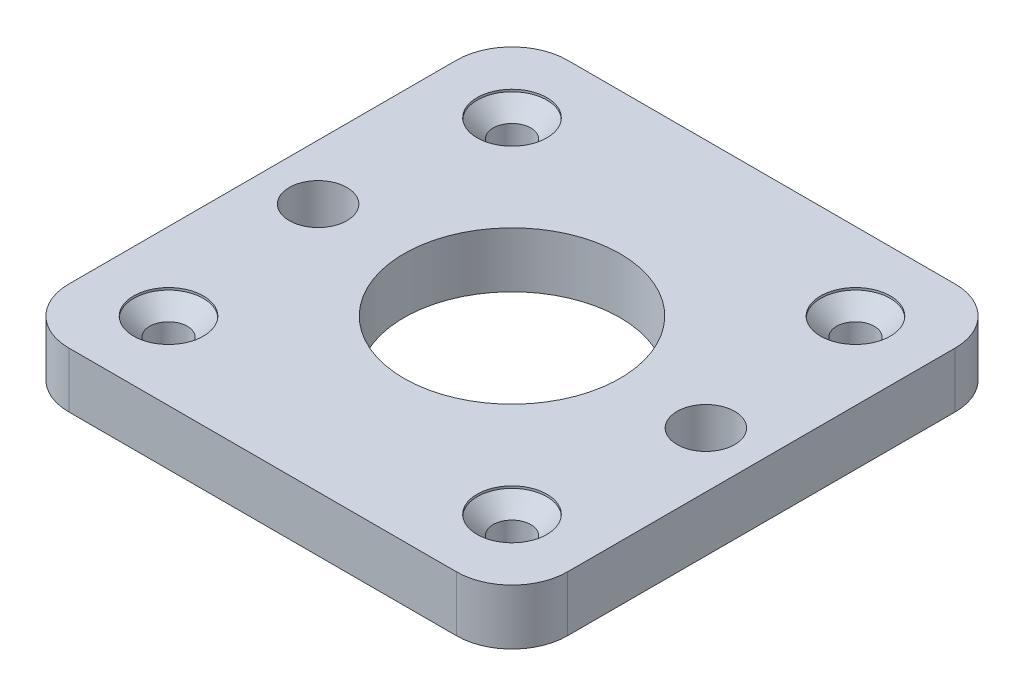
SolidWorks part; units mm, degrees
material "AISI 1020"
ref_plane "Plano frontal" through (0, 0, 0) normal (0, 0, 1) x (1, 0, 0)
ref_plane "Plano superior" through (0, 0, 0) normal (0, 1, 0) x (1, 0, 0)
ref_plane "Plano direito" through (0, 0, 0) normal (1, 0, 0) x (0, 0, -1)
sketch "Esboço1" plane through (0, 0, 0) normal (0, 1, 0) x (1, 0, 0)
  line L1 (-22.5, 22.5) -> (22.5, 22.5)
  line L2 (-22.5, 22.5) -> (-22.5, -22.5)
  line L3 (-22.5, -22.5) -> (22.5, -22.5)
  line L4 (22.5, 22.5) -> (22.5, -22.5)
  line L5 (-22.5, 22.5) -> (22.5, -22.5) construction
  line L6 (-22.5, -22.5) -> (22.5, 22.5) construction
  circle A0 centre (0, 0) radius 9.75
  point P0 (0, 0)
  dimension "D2" = 19.5
  dimension "D1" = 45
extrude "Ressalto-extrusão1" add sketch "Esboço1" along normal mid plane 5
hole_wizard "Escareado para parafuso com cabeça escareada elevada de M31" positions "Esboço3" profile "Esboço4" countersink size "M3" standard "Din" end condition through all
sketch "Esboço3" plane through (0, 2.5, 0) normal (0, 1, 0) x (1, 0, 0)
  line L0 (-15.5, 15.5) -> (0, 0) construction
  line L1 (0, 0) -> (0, 21.9203) construction
  line L3 (0, 0) -> (21.9203, 0) construction
  circle A0 centre (0, 0) radius 21.9203 construction
  point P0 (-15.5, 15.5)
  point P13 (15.5, 15.5)
  point P19 (15.5, -15.5)
  point P20 (-15.5, -15.5)
  dimension "D1" = 45
  dimension "D2" = 31
sketch "Esboço4" plane through (-15.5, 2.5, -15.5) normal (1, 0, 0) x (0, 0, 1)
  line L0 (0, 0) -> (0, 5)
  line L1 (0, 5) -> (1.725, 5)
  line L3 (1.7, 1.65) -> (3.15, 0.2)
  line L4 (3.15, 0.2) -> (3.15, 0)
  line L6 (3.15, 0) -> (0, 0)
  line L7 (-1.7, 1.65) -> (-3.15, 0.2) construction
  line L8 (1.725, 5) -> (1.7, 4.975)
  line L9 (1.7, 4.975) -> (1.7, 1.65)
  line L10 (-1.725, 5) -> (-1.7, 4.975) construction
  line L11 (0, -6.35) -> (0, 107.95) construction
  dimension "Thru Hole Dia." = 3.4
  dimension "Thru Hole Depth" = 5
  dimension "C'Sink Dia." = 6.3
  dimension "C'Sink Angle" = 90
  dimension "Far C'Sink Dia." = 3.45
  dimension "Far C'Sink Angle" = 90
  dimension "Head Clearance" = 0.2
fillet "Filete1" radius 5 4 edges at (22.5, 0, 22.5) (-22.5, 0, 22.5) (-22.5, 0, -22.5) (22.5, 0, -22.5)
hole_wizard "Furo de diâmetro Ø5.2 (5.2)1" positions "Esboço6" profile "Esboço5" hole size "Ø5.2" standard "Din"
sketch "Esboço6" plane through (0, -2.5, 0) normal (0, -1, 0) x (-1, 0, 0)
  line L0 (0, 0) -> (-17.5, 0) construction
  line L2 (-22.5, -17.5) -> (-22.5, 17.5) construction
  point P0 (-17.5, 0)
  dimension "D1" = 5
sketch "Esboço5" plane through (17.5, -2.5, 0) normal (1, 0, 0) x (0, 0, -1)
  line L0 (0, 0) -> (0, 47.5622)
  line L1 (0, 47.5622) -> (2.6, 46)
  line L2 (2.6, 46) -> (2.6, 0)
  line L5 (2.6, 0) -> (0, 0)
  line L10 (0, 47.5622) -> (-2.6, 46) construction
  line L11 (0, -6.35) -> (0, 107.95) construction
  dimension "Hole Dia." = 5.2
  dimension "Hole Depth" = 46
  dimension "Drill Angle" = 118
mirror "Espelhar1" about plane through (0, 0, 0) normal (1, 0, 0) of "Furo de diâmetro Ø5.2 (5.2)1"
